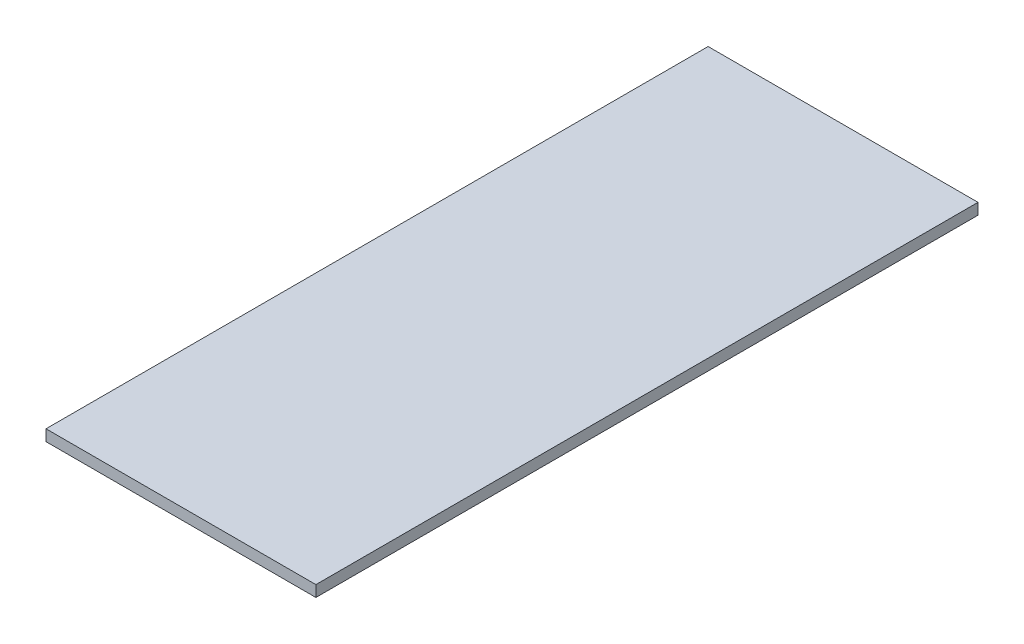
SolidWorks part; units mm, degrees
ref_plane "Front Plane" through (0, 0, 0) normal (0, 0, 1) x (1, 0, 0)
ref_plane "Top Plane" through (0, 0, 0) normal (0, 1, 0) x (1, 0, 0)
ref_plane "Right Plane" through (0, 0, 0) normal (1, 0, 0) x (0, 0, -1)
sketch "Sketch1" plane through (0, 0, 0) normal (0, 1, 0) x (1, 0, 0)
  line L1 (-30.6734, -75.2511) -> (30.6734, -75.2511)
  line L2 (-30.6734, -75.2511) -> (-30.6734, 75.2511)
  line L3 (-30.6734, 75.2511) -> (30.6734, 75.2511)
  line L4 (30.6734, -75.2511) -> (30.6734, 75.2511)
  line L5 (-30.6734, -75.2511) -> (30.6734, 75.2511) construction
  line L6 (-30.6734, 75.2511) -> (30.6734, -75.2511) construction
  point P0 (0, 0)
extrude "Boss-Extrude1" add sketch "Sketch1" along normal blind 2.54 contours L3 L4 L1 L2
